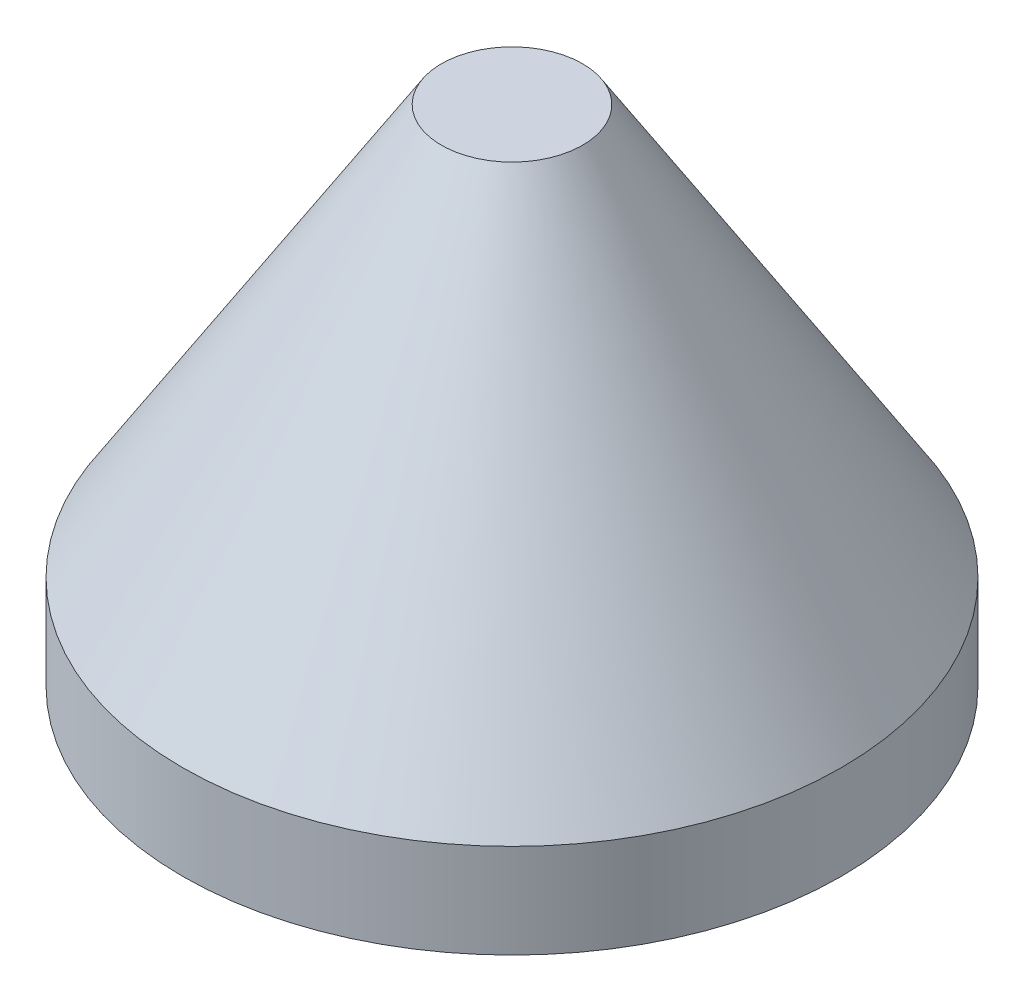
SolidWorks part; units mm, degrees
ref_plane "前视基准面" through (0, 0, 0) normal (0, 0, 1) x (1, 0, 0)
ref_plane "上视基准面" through (0, 0, 0) normal (0, 1, 0) x (1, 0, 0)
ref_plane "右视基准面" through (0, 0, 0) normal (1, 0, 0) x (0, 0, -1)
sketch "草图1" plane through (0, 0, 0) normal (0, 1, 0) x (1, 0, 0)
  circle A0 centre (0, 0) radius 14
  dimension "D1" = 28
extrude "凸台-拉伸1" add sketch "草图1" along normal blind 21.4
sketch "草图2" plane through (0, 0, 0) normal (0, 0, 1) x (1, 0, 0)
  line L0 (3, 21.4) -> (14, 21.4)
  line L1 (14, 21.4) -> (-14, 21.4) construction
  line L2 (14, 21.4) -> (14, 4)
  line L3 (14, 0) -> (14, 21.4) construction
  line L4 (14, 4) -> (3, 21.4)
  line L5 (-14, 0) -> (14, 0) construction
  line L6 (0, 0) -> (0, 21.0409) construction
  dimension "D1" = 3
  dimension "D2" = 4
revolve "切除-旋转1" cut sketch "草图2" angle 360 about L6
sketch "草图3" plane through (0, 0, 0) normal (0, -1, 0) x (1, 0, 0)
  circle A1 centre (0, 0) radius 14
  circle A2 centre (0, 0) radius 14
  dimension "D1" = 0
extrude "凸台-拉伸2" [suppressed] add sketch "草图3" along normal blind 0.8
